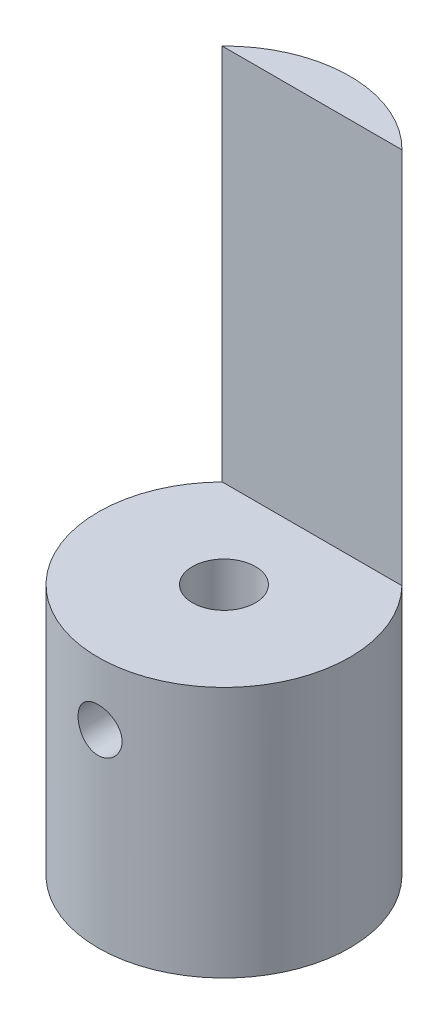
SolidWorks part; units mm, degrees
ref_plane "Alzado" through (0, 0, 0) normal (0, 0, 1) x (1, 0, 0)
ref_plane "Planta" through (0, 0, 0) normal (0, 1, 0) x (1, 0, 0)
ref_plane "Vista lateral" through (0, 0, 0) normal (1, 0, 0) x (0, 0, -1)
sketch "Croquis1" plane through (0, 0, 0) normal (0, 1, 0) x (1, 0, 0)
  circle A0 centre (0, 0) radius 10
  dimension "D1" = 20
extrude "Saliente-Extruir1" add sketch "Croquis1" along normal mid plane 50
sketch "Croquis3" plane through (0, 25, 0) normal (0, 1, 0) x (1, 0, 0)
  circle A0 centre (0, 0) radius 10 construction
  circle A1 centre (0, 0) radius 2.5
  dimension "D1" = 5
extrude "Cortar-Extruir2" cut sketch "Croquis3" against normal through all
sketch "Croquis2" plane through (0, 25, 0) normal (0, 1, 0) x (1, 0, 0)
  line L1 (-7.1414, 7) -> (7.1414, 7)
  arc A0 (-7.1414, 7) -> (7.1414, 7) centre (0, 0) ccw
  point P5 (-10, 7)
  point P6 (10, 7)
  dimension "D2" = 10
  dimension "D1" = 7
extrude "Cortar-Extruir1" cut sketch "Croquis2" against normal blind 30
ref_plane "Plano1" through (0, -5, 10) normal (0, 0, 1) x (1, 0, 0)
sketch "Croquis7" plane through (0, -5, 10) normal (0, 0, 1) x (1, 0, 0)
  line L0 (10, 0) -> (-10, 0) construction
  line L1 (0, 5) -> (0, -5) construction
  circle A0 centre (0, -5) radius 1.75
  dimension "D2" = 3.5
  dimension "D1" = 5
extrude "Cortar-Extruir3" cut sketch "Croquis7" against normal up to next
cosmetic thread "Rosca cosmética2" parameters "D2"=4
ref_plane "Plano2" through (0, 0, 0) normal (-1, 0, 0) x (0, 0, 1)
